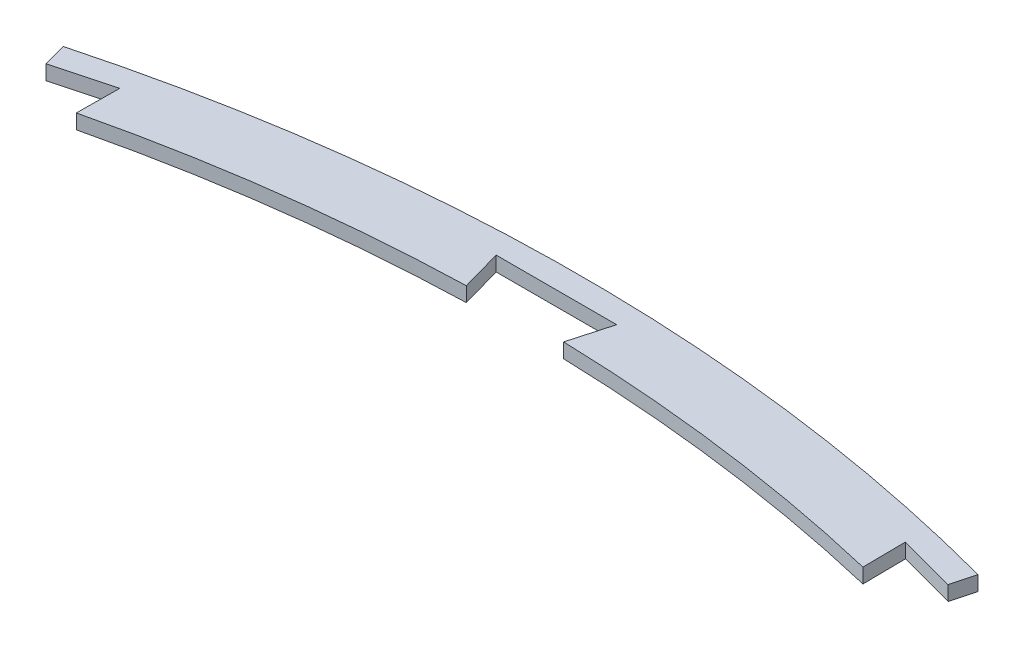
SolidWorks part; units mm, degrees
ref_plane "Front Plane" through (0, 0, 0) normal (0, 0, 1) x (1, 0, 0)
ref_plane "Top Plane" through (0, 0, 0) normal (0, 1, 0) x (1, 0, 0)
ref_plane "Right Plane" through (0, 0, 0) normal (1, 0, 0) x (0, 0, -1)
sketch "Sketch1" plane through (0, 0, 0) normal (0, 1, 0) x (1, 0, 0)
  line L0 (0, 0) -> (-280.8187, 1048.0295)
  line L1 (-280.8187, 1085) -> (280.8187, 1085) construction
  line L2 (-280.8187, 1085) -> (-280.8187, 785) construction
  line L3 (-280.8187, 785) -> (280.8187, 785) construction
  line L4 (280.8187, 1085) -> (280.8187, 785) construction
  line L5 (0, 0) -> (280.8187, 1048.0295)
  line L6 (0, 1020) -> (0, 0) construction
  line L7 (-37, 1070) -> (37, 1070)
  line L8 (-37, 1070) -> (-30, 1045)
  line L9 (955, 0) -> (1000, 0) construction
  line L10 (1000, 0) -> (1045, 0) construction
  line L11 (-30, 1045) -> (-29.8804, 1044.5727)
  line L12 (30, 1045) -> (29.8804, 1044.5727)
  line L13 (-276.9364, 1033.5406) -> (-241.1971, 1043.1169)
  line L14 (-241.1971, 1043.1169) -> (-241.4881, 1017.1571)
  line L15 (-241.4881, 1017.1571) -> (-241.4931, 1016.7134)
  line L16 (241.1971, 1043.1169) -> (241.4881, 1017.1571)
  line L17 (276.9364, 1033.5406) -> (241.1971, 1043.1169)
  line L18 (37, 1070) -> (30, 1045)
  line L19 (241.4881, 1017.1571) -> (241.4931, 1016.7134)
  line L20 (241.1971, 1043.1169) -> (241.4881, 1017.1571)
  line L21 (276.9364, 1033.5406) -> (241.1971, 1043.1169)
  circle A0 centre (0, 0) radius 1085
  circle A1 centre (0, 0) radius 1045
  circle A2 centre (0, 0) radius 955
  circle A3 centre (0, 0) radius 915
  circle A6 centre (0, 0) radius 1065 construction
  circle A7 centre (0, 0) radius 935 construction
  circle A9 centre (-227.4758, 906.9067) radius 4
  circle A10 centre (227.4758, 906.9067) radius 4
  circle A12 centre (0, 0) radius 1032.5 construction
  circle A15 centre (0, 0) radius 1000 construction
  point P12 (0, 785)
  point P28 (0, 1070)
  point P40 (-241.3426, 1030.137)
  point P45 (0, 1070)
  point P47 (241.3426, 1030.137)
  dimension "D11" = 8
  dimension "D8" = 2000
  dimension "D1" = 300
  dimension "D3" = 40
  dimension "D4" = 40
  dimension "D5" = 20
  dimension "D6" = 20
  dimension "D12" = 15
  dimension "D7" = 170
  dimension "D2" = 15
  dimension "D13" = 15
  dimension "D14" = 12.5
  dimension "D9" = 37
  dimension "D10" = 30
  dimension "D16" = 1070
  dimension "D17" = 90
  dimension "D18" = 37
  dimension "D19" = 1070
  dimension "D20" = 25
  dimension "D21" = 30
  dimension "D15" = 25
extrude "Boss-Extrude1" add sketch "Sketch1" along normal blind 9
equation "\"D19@Sketch1\"=2170/2-15"
equation "\"D16@Sketch1\"=2170/2-15"
